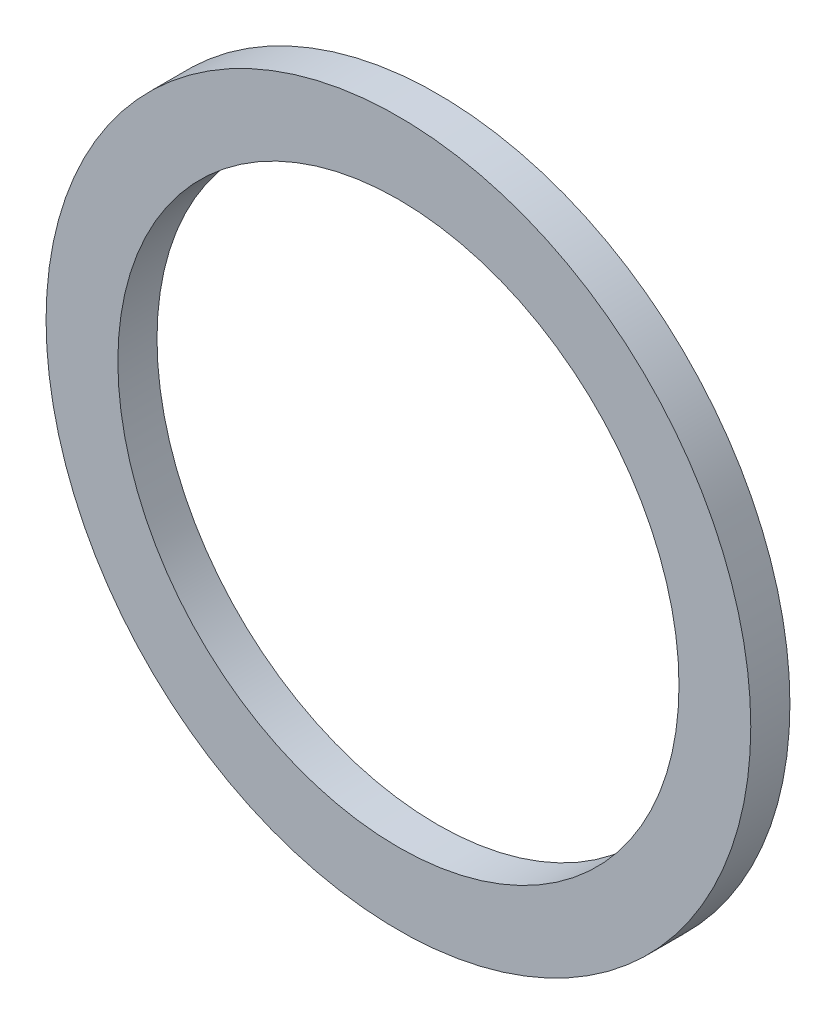
SolidWorks part; units mm, degrees
ref_plane "Plan1" through (0, 0, 0) normal (0, 0, 1) x (1, 0, 0)
ref_plane "Plan2" through (0, 0, 0) normal (0, 1, 0) x (1, 0, 0)
ref_plane "Plan3" through (0, 0, 0) normal (1, 0, 0) x (0, 0, -1)
sketch "Esquisse1" plane through (0, 0, 0) normal (0, 0, 1) x (1, 0, 0)
  circle A0 centre (0, 0) radius 10.75
  circle A1 centre (0, 0) radius 13.5
  dimension "D1" = 21.5
  dimension "D2" = 27
extrude "Base-Extrusion" add sketch "Esquisse1" along normal blind 1.5
